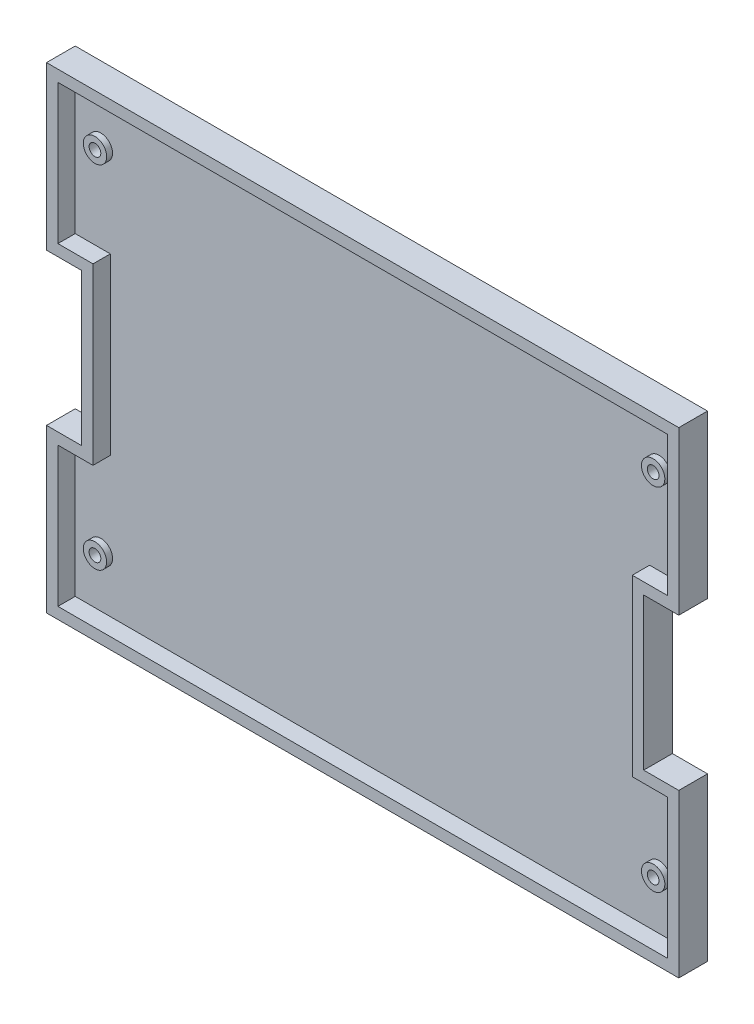
SolidWorks part; units mm, degrees
ref_plane "Alzado" through (0, 0, 0) normal (0, 0, 1) x (1, 0, 0)
ref_plane "Planta" through (0, 0, 0) normal (0, 1, 0) x (1, 0, 0)
ref_plane "Vista lateral" through (0, 0, 0) normal (1, 0, 0) x (0, 0, -1)
sketch "Croquis1" plane through (0, 0, 0) normal (0, 0, 1) x (1, 0, 0)
  line L0 (-54.055, 0) -> (54.055, 0) construction
  line L1 (-54.055, -40.75) -> (54.055, -40.75)
  line L2 (-54.055, -40.75) -> (-54.055, 40.75)
  line L3 (-54.055, 40.75) -> (54.055, 40.75)
  line L4 (54.055, -40.75) -> (54.055, 40.75)
  line L5 (-54.055, -40.75) -> (54.055, 40.75) construction
  line L6 (-54.055, 40.75) -> (54.055, -40.75) construction
  line L7 (-48.055, -12.97) -> (-48.055, 12.97)
  line L8 (-48.055, 12.97) -> (-54.055, 12.97)
  line L9 (-48.055, -12.97) -> (-54.055, -12.97)
  line L10 (-54.055, 12.97) -> (-54.055, -12.97)
  line L11 (0, 40.75) -> (0, -40.75) construction
  line L12 (54.055, 12.97) -> (54.055, -12.97)
  line L13 (48.055, -12.97) -> (54.055, -12.97)
  line L14 (48.055, 12.97) -> (54.055, 12.97)
  line L15 (48.055, -12.97) -> (48.055, 12.97)
  point P0 (0, 0)
  point P11 (-48.055, 0)
  point P19 (48.055, 0)
  dimension "D1" = 81.5
  dimension "D2" = 108.11
  dimension "D3" = 6
  dimension "D4" = 25.94
extrude "Saliente-Extruir1" add sketch "Croquis1" along normal blind 4.91 contours L13 L15 L14 L4 L3 L2 L8 L7 L9 L1
shell "Vaciado1" thickness 1.95
sketch "Croquis3" plane through (0, 0, 0) normal (0, 0, 1) x (1, 0, 0)
  line L0 (-46.105, 0) -> (46.105, 0) construction
  line L1 (-46.105, -14.92) -> (-46.105, 14.92) construction
  line L2 (46.105, -14.92) -> (46.105, 14.92) construction
  line L3 (0, 38.8) -> (0, -38.8) construction
  line L4 (-52.105, 38.8) -> (52.105, 38.8) construction
  line L5 (-52.105, -38.8) -> (52.105, -38.8) construction
  circle A3 centre (-47.72, 30.01) radius 2
  circle A5 centre (47.72, 30.01) radius 2
  circle A6 centre (47.72, -30.01) radius 2
  circle A7 centre (-47.72, -30.01) radius 2
  dimension "D1" = 30.01
  dimension "D2" = 47.72
extrude "Saliente-Extruir3" add sketch "Croquis3" along direction (0, 0, 1) on the side of the normal blind 2.96
sketch "Croquis4" plane through (0, 0, 0) normal (0, 0, 1) x (1, 0, 0)
  line L0 (-46.105, 0) -> (46.105, 0) construction
  line L1 (-46.105, -14.92) -> (-46.105, 14.92) construction
  line L2 (46.105, -14.92) -> (46.105, 14.92) construction
  line L3 (0, 38.8) -> (0, -38.8) construction
  line L4 (-52.105, 38.8) -> (52.105, 38.8) construction
  line L5 (-52.105, -38.8) -> (52.105, -38.8) construction
  circle A0 centre (-47.72, 30.01) radius 1
  circle A1 centre (47.72, 30.01) radius 1
  circle A2 centre (47.72, -30.01) radius 1
  circle A3 centre (-47.72, -30.01) radius 1
extrude "Cortar-Extruir1" cut sketch "Croquis4" against normal blind 2.96 and the other way through all
